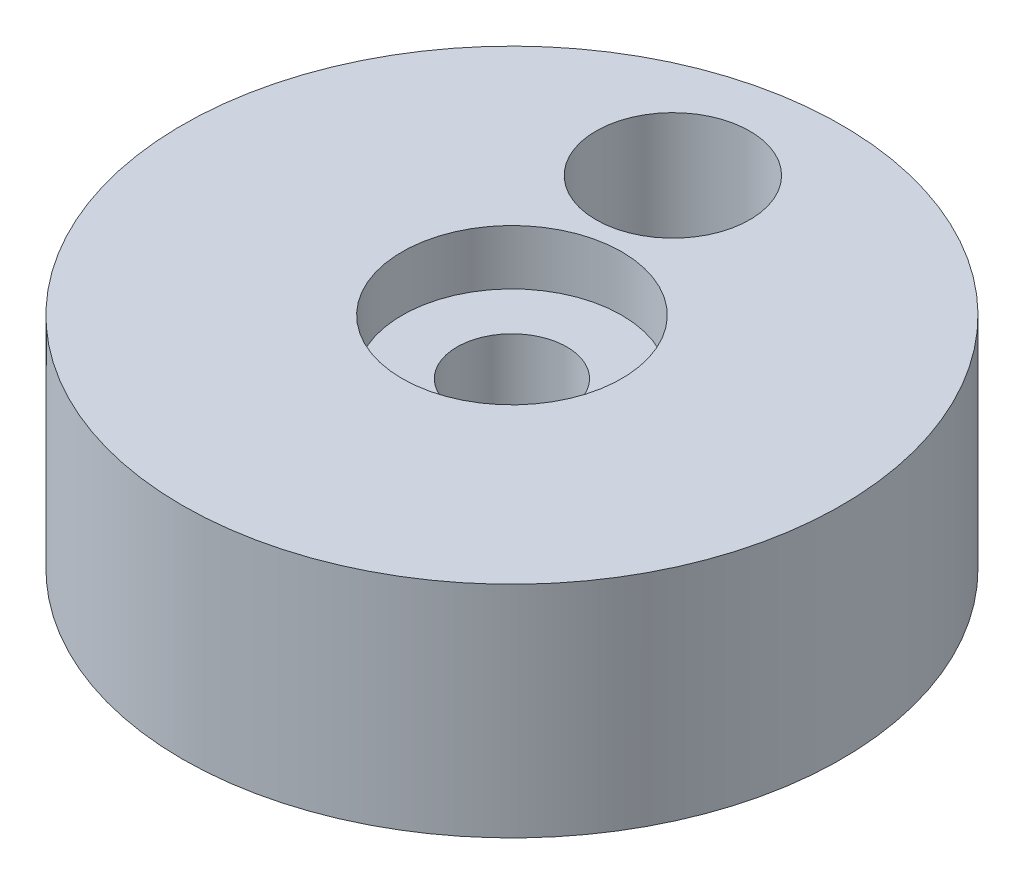
SolidWorks part; units mm, degrees
ref_plane "Front Plane" through (0, 0, 0) normal (0, 0, 1) x (1, 0, 0)
ref_plane "Top Plane" through (0, 0, 0) normal (0, 1, 0) x (1, 0, 0)
ref_plane "Right Plane" through (0, 0, 0) normal (1, 0, 0) x (0, 0, -1)
sketch "Sketch1" plane through (0, 0, 0) normal (0, 1, 0) x (1, 0, 0)
  circle A0 centre (0, 0) radius 19.05
  dimension "D1" = 38.1
extrude "Boss-Extrude1" add sketch "Sketch1" against normal blind 12.7
sketch "Sketch2" plane through (0, 0, 0) normal (0, 1, 0) x (1, 0, 0)
  circle A0 centre (0, 0) radius 3.175
  dimension "D1" = 6.35
extrude "Cut-Extrude1" cut sketch "Sketch2" against normal blind 17.78
sketch "Sketch3" plane through (0, 0, 0) normal (0, 1, 0) x (1, 0, 0)
  circle A0 centre (0, 0) radius 6.35
  dimension "D1" = 12.7
extrude "Cut-Extrude2" cut sketch "Sketch3" against normal blind 3.175
sketch "Sketch4" plane through (0, 0, 0) normal (0, 1, 0) x (1, 0, 0)
  circle A0 centre (-2.346, 11.6486) radius 4.445
  dimension "D1" = 8.89
extrude "Cut-Extrude3" cut sketch "Sketch4" against normal blind 38.1
sketch "Sketch5" plane through (0, -12.7, 0) normal (0, 1, 0) x (1, 0, 0)
  circle A0 centre (-13.4003, 17.901) radius 6.604
  circle A2 centre (-13.4003, 17.901) radius 6.35 construction
  dimension "D1" = 13.208
extrude "Cut-Extrude4" cut sketch "Sketch5" along normal blind 6.35
